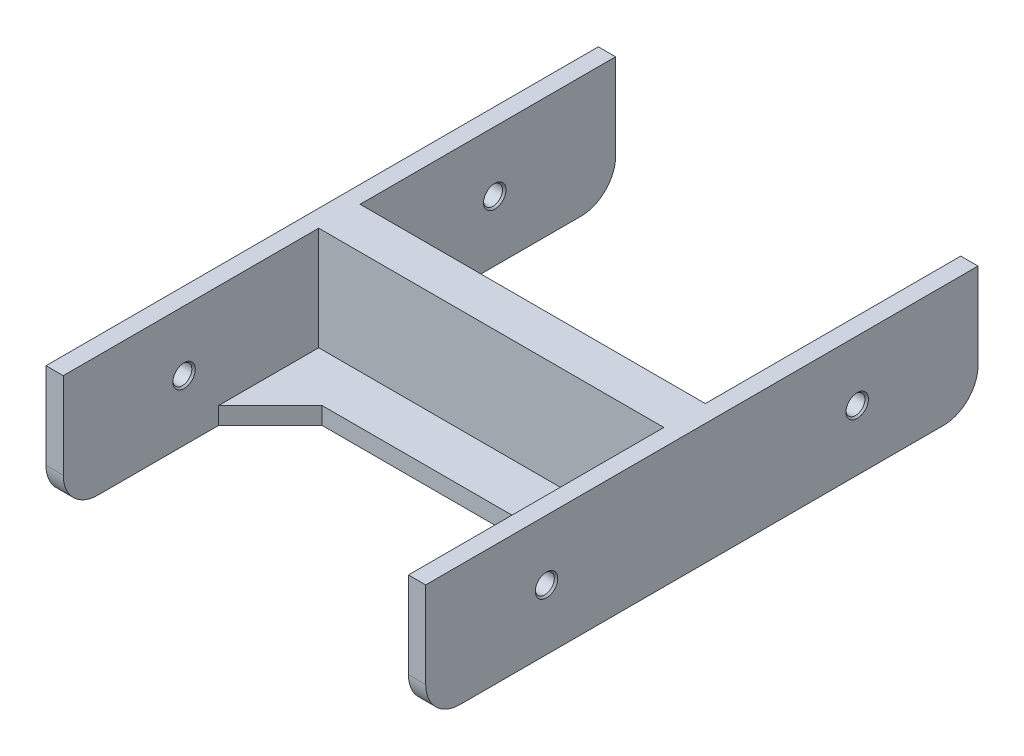
SolidWorks part; units mm, degrees
ref_plane "前视基准面" through (0, 0, 0) normal (0, 0, 1) x (1, 0, 0)
ref_plane "上视基准面" through (0, 0, 0) normal (0, 1, 0) x (1, 0, 0)
ref_plane "右视基准面" through (0, 0, 0) normal (1, 0, 0) x (0, 0, -1)
sketch "草图1" plane through (0, 0, 0) normal (1, 0, 0) x (0, 0, -1)
  line L1 (-80, 5) -> (80, 5)
  line L2 (-80, 5) -> (-80, -15)
  line L3 (-80, -15) -> (80, -15)
  line L4 (80, 5) -> (80, -15)
  dimension "D1" = 160
  dimension "D2" = 80
  dimension "D3" = 20
  dimension "D4" = 5
extrude "凸台-拉伸1" add sketch "草图1" along normal blind 5
sketch "草图3" plane through (5, 0, 0) normal (1, 0, 0) x (0, 0, -1)
  line L6 (-6, 5) -> (6, 5)
  line L7 (80, 5) -> (-80, 5) construction
  line L8 (6, 5) -> (6, -10)
  line L9 (6, -10) -> (20, -10)
  line L10 (20, -10) -> (20, -15)
  line L11 (-80, -15) -> (80, -15) construction
  line L12 (20, -15) -> (-20, -15)
  line L13 (-20, -15) -> (-20, -10)
  line L14 (-20, -10) -> (-6, -10)
  line L15 (-6, -10) -> (-6, 5)
  dimension "D1" = 6
  dimension "D2" = 6
  dimension "D3" = 5
  dimension "D4" = 5
  dimension "D5" = 20
  dimension "D6" = 20
extrude "凸台-拉伸3" add sketch "草图3" along normal blind 100
sketch "草图5" plane through (0, 0, 0) normal (-1, 0, 0) x (0, 0, 1)
  line L0 (-6, -10) -> (-6, 5) construction
  line L1 (6, 5) -> (-6, 5)
  line L2 (6, 5) -> (6, 20)
  line L3 (6, 20) -> (-6, 20)
  line L4 (-6, 5) -> (-6, 20)
  dimension "D1" = 15
extrude "凸台-拉伸4" add sketch "草图5" against normal blind 105
sketch "草图6" plane through (0, 0, 0) normal (-1, 0, 0) x (0, 0, 1)
  line L1 (6, 20) -> (80, 20)
  line L2 (6, 20) -> (6, 5)
  line L3 (6, 5) -> (80, 5)
  line L4 (80, 20) -> (80, 5)
  line L5 (-6, 20) -> (-80, 20)
  line L6 (-6, 20) -> (-6, 5)
  line L7 (-6, 5) -> (-80, 5)
  line L8 (-80, 20) -> (-80, 5)
extrude "凸台-拉伸5" add sketch "草图6" against normal blind 5
sketch "草图7" plane through (105, 0, 0) normal (1, 0, 0) x (0, 0, -1)
  line L1 (-80, -15) -> (80, -15)
  line L2 (-80, -15) -> (-80, 20)
  line L3 (-80, 20) -> (80, 20)
  line L4 (80, -15) -> (80, 20)
extrude "凸台-拉伸6" add sketch "草图7" along normal blind 5
sketch "草图8" plane through (0, -15, 0) normal (0, -1, 0) x (1, 0, 0)
  line L0 (90, 20) -> (105, 35)
  line L1 (105, 20) -> (5, 20) construction
  line L2 (105, 80) -> (105, 20) construction
  line L3 (105, 35) -> (105, 20)
  line L4 (105, 20) -> (90, 20)
  line L5 (0, 0) -> (50000, 0) construction
  line L6 (55, 20) -> (55, 50020) construction
  line L7 (105, -20) -> (90, -20)
  line L8 (105, -35) -> (105, -20)
  line L9 (90, -20) -> (105, -35)
  line L10 (5, 20) -> (20, 20)
  line L11 (5, 35) -> (5, 20)
  line L12 (20, 20) -> (5, 35)
  line L13 (20, -20) -> (5, -35)
  line L14 (5, -35) -> (5, -20)
  line L15 (5, -20) -> (20, -20)
  point P13 (55, 20)
  dimension "D1" = 15
  dimension "D2" = 15
extrude "凸台-拉伸7" add sketch "草图8" against normal blind 5
sketch "草图9" plane through (110, 0, 0) normal (1, 0, 0) x (0, 0, -1)
  line L0 (0, 0) -> (0, -50000) construction
  line L1 (80, 20) -> (-80, 20) construction
  circle A0 centre (45, 2.5) radius 2.75
  circle A1 centre (-45, 2.5) radius 2.75
  dimension "D1" = 5.5
  dimension "D2" = 17.5
  dimension "D3" = 45
extrude "切除-拉伸1" cut sketch "草图9" against normal through all
chamfer "倒角1" distance 0.5 angle 45 8 edges at (105, 2.5, -42.25) (5, 2.5, -47.75) (0, 2.5, -47.75) (110, 2.5, -47.75) (105, 2.5, 47.75) (5, 2.5, 42.25) (0, 2.5, 47.75) (110, 2.5, 47.75)
fillet "圆角1" radius 10 4 edges at (107.5, -15, -80) (107.5, -15, 80) (2.5, -15, 80) (2.5, -15, -80)
